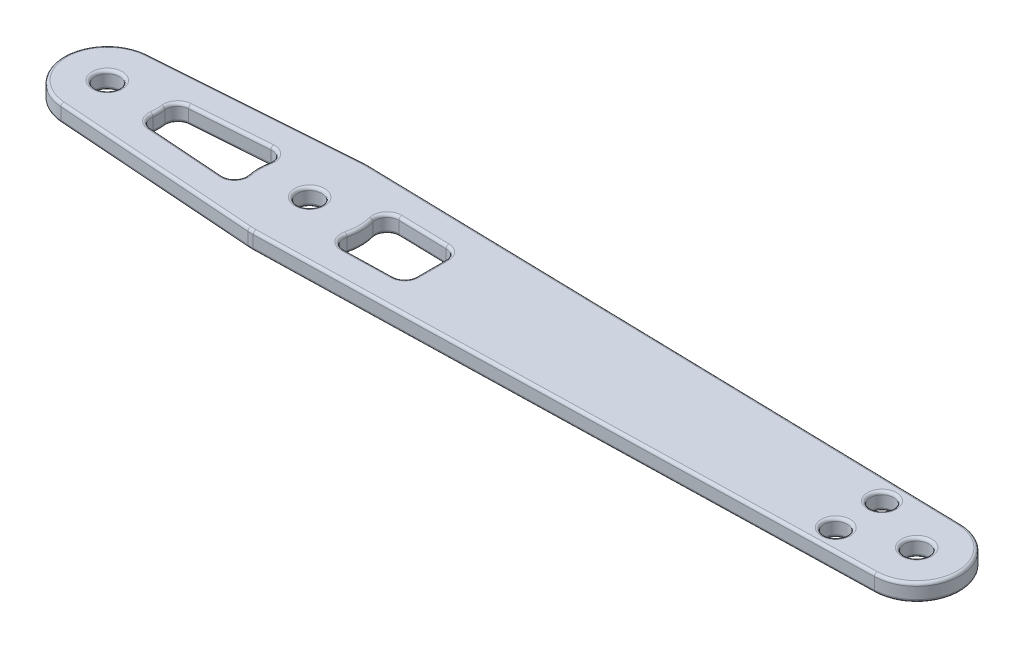
SolidWorks part; units mm, degrees
ref_plane "Front Plane" through (0, 0, 0) normal (0, 0, 1) x (1, 0, 0)
ref_plane "Top Plane" through (0, 0, 0) normal (0, 1, 0) x (1, 0, 0)
ref_plane "Right Plane" through (0, 0, 0) normal (1, 0, 0) x (0, 0, -1)
sketch "Sketch1" plane through (0, 0, 0) normal (0, 1, 0) x (1, 0, 0)
  line L0 (-0.5357, 7.4808) -> (34.2857, 9.9745)
  line L1 (-0.5357, -7.4808) -> (34.2857, -9.9745)
  line L2 (35.2381, 9.9972) -> (140.1786, 7.4979)
  line L3 (140.1786, -7.4979) -> (35.2381, -9.9972)
  circle A0 centre (0, 0) radius 2.1
  circle A1 centre (35, 0) radius 2.1
  circle A2 centre (140, 0) radius 2.1
  arc A3 (-0.5357, 7.4808) -> (-0.5357, -7.4808) centre (0, 0) ccw
  arc A4 (140.1786, -7.4979) -> (140.1786, 7.4979) centre (140, 0) ccw
  arc A5 (35.2381, 9.9972) -> (34.2857, 9.9745) centre (35, 0) ccw
  arc A6 (34.2857, -9.9745) -> (35.2381, -9.9972) centre (35, 0) ccw
  dimension "D1" = 4.2
  dimension "D2" = 4.2
  dimension "D4" = 4.2
  dimension "D6" = 15
  dimension "D7" = 15
  dimension "D8" = 20
  dimension "D3" = 35
  dimension "D5" = 140
extrude "Boss-Extrude1" add sketch "Sketch1" along normal blind 3
sketch "Sketch2" plane through (0, 3, 0) normal (0, 1, 0) x (1, 0, 0)
  line L2 (34.6429, 4.9872) -> (-0.1786, 2.4936)
  line L3 (24.0869, 4.2313) -> (10.782, 3.2785)
  line L5 (-0.1786, -2.4936) -> (34.6429, -4.9872)
  line L6 (10.782, -3.2785) -> (24.0869, -4.2313)
  line L8 (140.0595, 2.4993) -> (35.119, 4.9986)
  line L9 (130.1755, 2.7347) -> (122.0476, 2.9283) construction
  line L10 (120, 0.9288) -> (120, -0.9288) construction
  line L11 (35.119, -4.9986) -> (140.0595, -2.4993)
  line L12 (45.6991, -4.7466) -> (54.0476, -4.5478)
  line L13 (56, 2.5483) -> (56, -2.5483)
  line L14 (122.0476, -2.9283) -> (130.1755, -2.7347) construction
  line L15 (54.0476, 4.5478) -> (45.6991, 4.7466)
  arc A0 (8.9385, -1.0502) -> (8.9385, 1.0502) centre (0, 0) ccw
  arc A1 (43.7148, -2.2477) -> (43.7148, 2.2477) centre (35, 0) ccw
  arc A2 (131.1365, 1.5615) -> (131.1365, -1.5615) centre (140, 0) ccw construction
  circle A3 centre (35, 0) radius 2.1 construction
  arc A4 (26.188, 1.8298) -> (26.188, -1.8298) centre (35, 0) ccw
  arc A5 (122.0476, 2.9283) -> (120, 0.9288) centre (122, 0.9288) ccw construction
  arc A6 (122.0476, -2.9283) -> (120, -0.9288) centre (122, -0.9288) cw construction
  arc A7 (56, 2.5483) -> (54.0476, 4.5478) centre (54, 2.5483) ccw
  arc A8 (56, -2.5483) -> (54.0476, -4.5478) centre (54, -2.5483) cw
  arc A9 (43.7148, -2.2477) -> (45.6991, -4.7466) centre (45.6514, -2.7472) ccw
  arc A10 (43.7148, 2.2477) -> (45.6991, 4.7466) centre (45.6514, 2.7472) cw
  arc A11 (8.9385, -1.0502) -> (10.782, -3.2785) centre (10.9248, -1.2836) ccw
  arc A12 (8.9385, 1.0502) -> (10.782, 3.2785) centre (10.9248, 1.2836) cw
  arc A13 (24.0869, -4.2313) -> (26.188, -1.8298) centre (24.2297, -2.2364) ccw
  arc A14 (26.188, 1.8298) -> (24.0869, 4.2313) centre (24.2297, 2.2364) ccw
  arc A15 (131.1365, 1.5615) -> (130.1755, 2.7347) centre (130.1517, 1.735) ccw construction
  arc A16 (131.1365, -1.5615) -> (130.1755, -2.7347) centre (130.1517, -1.735) cw construction
  point P34 (56, 4.5013)
  dimension "D1" = 18
  dimension "D4" = 18
  dimension "D7" = 18
  dimension "D10" = 2
  dimension "D11" = 1
  dimension "D8" = 20
  dimension "D9" = 21
  dimension "D2" = 5
  dimension "D3" = 5
  dimension "D5" = 5
  dimension "D6" = 5
extrude "Cut-Extrude1" cut sketch "Sketch2" against normal blind 6
sketch "Sketch4" plane through (0, 3, 0) normal (0, 1, 0) x (1, 0, 0)
  line L0 (140, 0) -> (165.4974, 0) construction
  circle A0 centre (130, 4) radius 2
  circle A1 centre (140, 0) radius 2.1 construction
  circle A2 centre (130, -4) radius 2
  dimension "D1" = 4
  dimension "D2" = 4
  dimension "D3" = 10
extrude "Cut-Extrude2" cut sketch "Sketch4" against normal through all
fillet "Fillet1" radius 0.5 58 edges at (49.8733, 0, 4.6472) (44.0852, 0, 3.9909) (44, 0, 0) (44.0852, 0, -3.9909) (49.8733, 0, -4.6472) (55.431, 0, -3.9456) (56, 0, 0) (49.8733, 3, 4.6472) (44.0852, 3, 3.9909) (44, 3, 0) (44.0852, 3, -3.9909) (49.8733, 3, -4.6472) (55.431, 3, -3.9456) (56, 3, 0) (17.4344, 0, 3.7549) (9.3839, 0, 2.5585) (9, 0, 0) (9.3839, 0, -2.5585) (17.4344, 0, -3.7549) (25.735, 0, -3.5533) (26, 0, 0) (17.4344, 3, 3.7549) (9.3839, 3, 2.5585) (9, 3, 0) (9.3839, 3, -2.5585) (17.4344, 3, -3.7549) (25.735, 3, -3.5533) (26, 3, 0) (34.7616, 3, -9.9972) (87.7083, 3, -8.7475) (147.5, 3, 0) (87.7083, 3, 8.7475) (34.7616, 3, 9.9972) (16.875, 3, 8.7277) (-7.5, 3, 0) (34.7616, 0, -9.9972) (87.7083, 0, -8.7475) (147.5, 0, 0) (87.7083, 0, 8.7475) (34.7616, 0, 9.9972) (16.875, 0, 8.7277) (-7.5, 0, 0) (140, 0, 2.1) (140, 3, 2.1) (130, 3, -2) (130, 0, -2) (130, 3, 2) (130, 0, 2) (55.431, 0, 3.9456) (55.431, 3, 3.9456) (25.735, 0, 3.5533) (25.735, 3, 3.5533) (0, 0, 2.1) (0, 3, 2.1) (35, 0, 2.1) (35, 3, 2.1) (16.875, 3, -8.7277) (16.875, 0, -8.7277)
